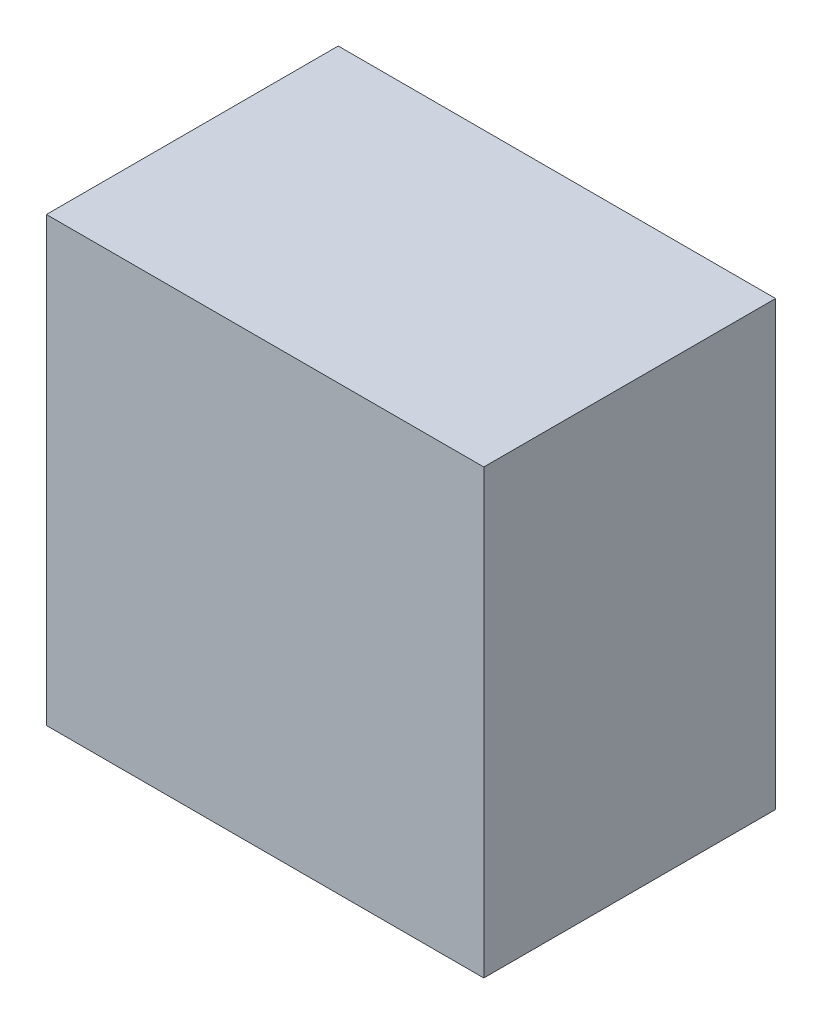
SolidWorks part; units mm, degrees
ref_plane "Front Plane" through (0, 0, 0) normal (0, 0, 1) x (1, 0, 0)
ref_plane "Top Plane" through (0, 0, 0) normal (0, 1, 0) x (1, 0, 0)
ref_plane "Right Plane" through (0, 0, 0) normal (1, 0, 0) x (0, 0, -1)
other "Configuration Table"
sketch "Sketch1" plane through (0, 0, 0) normal (0, 0, 1) x (1, 0, 0)
  line L1 (-45.5931, 23.5799) -> (29.3481, 23.5799)
  line L2 (-45.5931, 23.5799) -> (-45.5931, -52.2511)
  line L3 (-45.5931, -52.2511) -> (29.3481, -52.2511)
  line L4 (29.3481, 23.5799) -> (29.3481, -52.2511)
extrude "Boss-Extrude1" add sketch "Sketch1" along normal blind 50
sketch "Sketch2" plane through (0, 0, 50) normal (0, 0, 1) x (1, 0, 0)
  circle A0 centre (11.2129, -33.4455) radius 11.3713
sketch "Sketch3" plane through (29.3481, 0, 0) normal (1, 0, 0) x (0, 0, -1)
  line L0 (-50, -52.2511) -> (-50, 23.5799) construction
  line L1 (0, -52.2511) -> (0, 23.5799) construction
  spline S0 degree 2 poles (-50, -30.7191) (-21.2728, -1.7709) (0, -39.2363) knots 0 0 0 1 1 1
